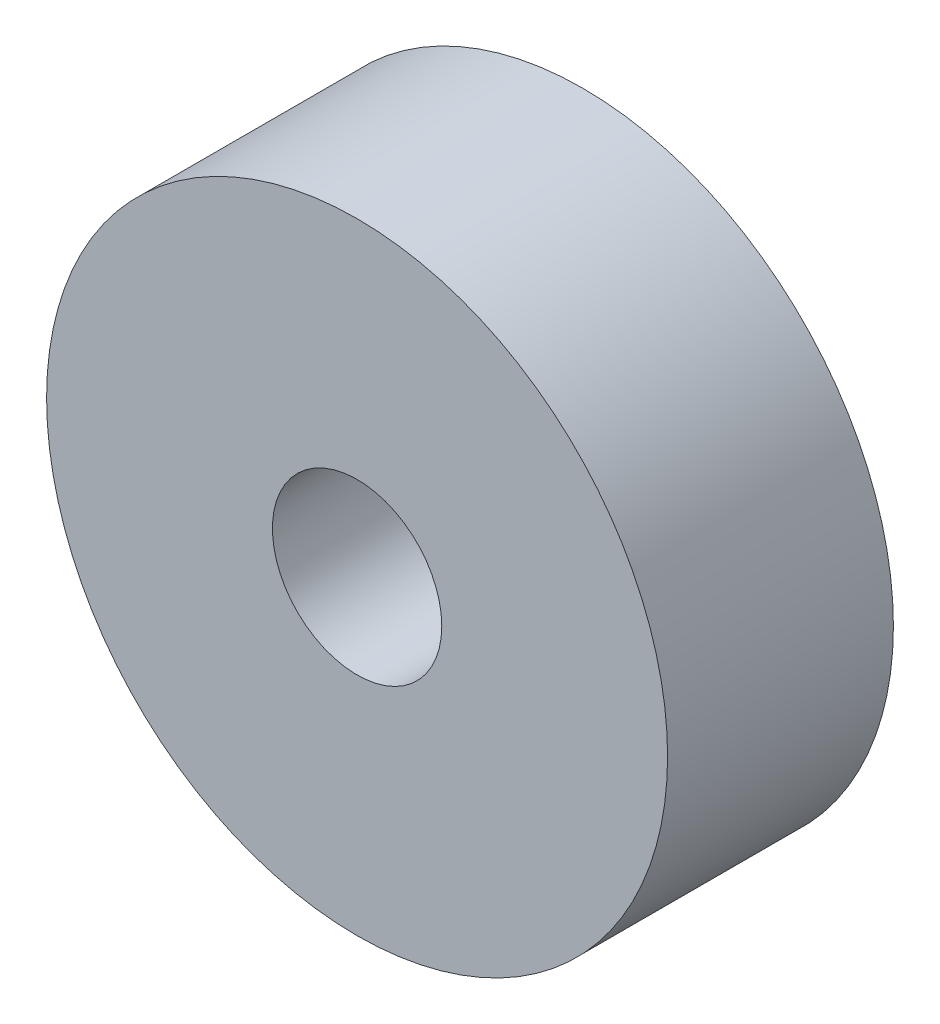
SolidWorks part; units mm, degrees
ref_plane "Front Plane" through (0, 0, 0) normal (0, 0, 1) x (1, 0, 0)
ref_plane "Top Plane" through (0, 0, 0) normal (0, 1, 0) x (1, 0, 0)
ref_plane "Right Plane" through (0, 0, 0) normal (1, 0, 0) x (0, 0, -1)
sketch "Sketch1" plane through (0, 0, 0) normal (0, 0, 1) x (1, 0, 0)
  circle A0 centre (0, 0) radius 8.7312
  circle A1 centre (0, 0) radius 2.3813
extrude "Boss-Extrude1" add sketch "Sketch1" along normal blind 6.35
